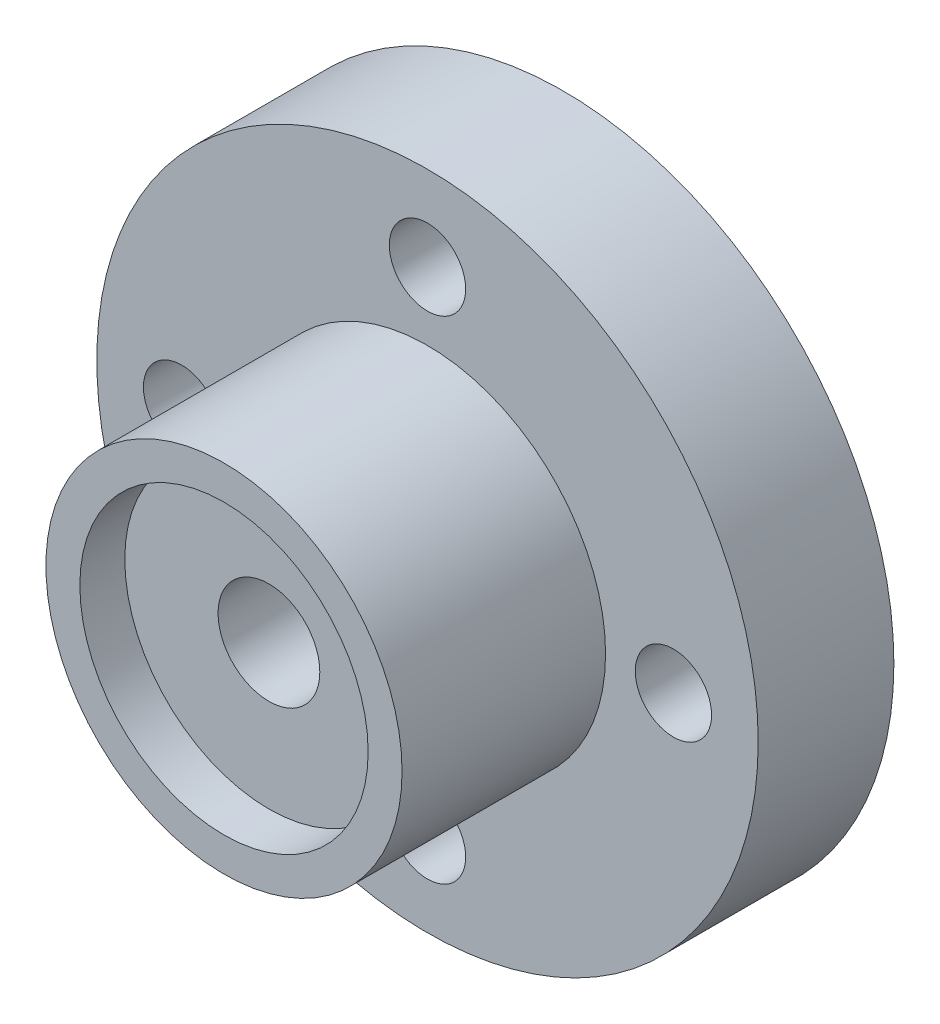
SolidWorks part; units mm, degrees
ref_plane "前视基准面" through (0, 0, 0) normal (0, 0, 1) x (1, 0, 0)
ref_plane "上视基准面" through (0, 0, 0) normal (0, 1, 0) x (1, 0, 0)
ref_plane "右视基准面" through (0, 0, 0) normal (1, 0, 0) x (0, 0, -1)
other "Configuration Table"
sketch "草图1" plane through (0, 0, 0) normal (0, 0, 1) x (1, 0, 0)
  circle A0 centre (0, 0) radius 19.5
  dimension "D1" = 39
extrude "凸台-拉伸1" add sketch "草图1" along normal blind 8
sketch "草图2" plane through (0, 0, 8) normal (0, 0, 1) x (1, 0, 0)
  circle A0 centre (0, 0) radius 10.5
  dimension "D1" = 21
extrude "凸台-拉伸2" add sketch "草图2" along normal blind 12
sketch "草图3" plane through (0, 0, 0) normal (0, 0, -1) x (-1, 0, 0)
  circle A0 centre (0, 0) radius 3
  dimension "D1" = 6
extrude "切除-拉伸1" cut sketch "草图3" against normal through all
sketch "草图4" plane through (0, 0, 20) normal (0, 0, 1) x (1, 0, 0)
  circle A0 centre (0, 0) radius 8.5
  circle A2 centre (0, 0) radius 10.5
  circle A3 centre (0, 0) radius 10.5
  dimension "D1" = 17
  dimension "D2" = 0
extrude "切除-拉伸3" cut sketch "草图4" against normal blind 2.65 contours A0
sketch "草图5" plane through (0, 0, 0) normal (0, 0, -1) x (-1, 0, 0)
  circle A0 centre (0, 0) radius 8.5
  dimension "D1" = 17
extrude "切除-拉伸4" cut sketch "草图5" against normal blind 2
hole_wizard "M4 六角圆柱头螺钉的柱形沉头孔1" positions "草图6" profile "草图7" counterbore size "M4" standard "GB" end condition through all
sketch "草图6" plane through (0, 0, 0) normal (0, 0, -1) x (-1, 0, 0)
  circle A0 centre (0, 0) radius 14.5 construction
  point P0 (0, 14.5)
  dimension "D1" = 29
sketch "草图7" plane through (0, 14.5, 0) normal (1, 0, 0) x (0, 1, 0)
  line L0 (0, 0) -> (0, 20)
  line L1 (0, 20) -> (2.25, 20)
  line L3 (2.25, 20) -> (2.25, 4.6)
  line L4 (4, 4.6) -> (2.25, 4.6)
  line L5 (4, 4.6) -> (4, 0.025)
  line L6 (4, 0.025) -> (4.025, 0)
  line L7 (4.025, 0) -> (0, 0)
  line L8 (-4, 0.025) -> (-4.025, 0) construction
  line L11 (0, -6.35) -> (0, 107.95) construction
  dimension "通孔孔直径" = 4.5
  dimension "通孔孔深度" = 20
  dimension "柱形沉头孔直径" = 8
  dimension "柱形沉头孔深度" = 4.6
  dimension "近端锥形沉头孔直径" = 8.05
  dimension "近端锥形沉头孔角度" = 90
pattern_circular "阵列(圆周)1" count 4 over 360 about axis through (0, 0, 0) along (0, 0, 1) of "M4 六角圆柱头螺钉的柱形沉头孔1"
